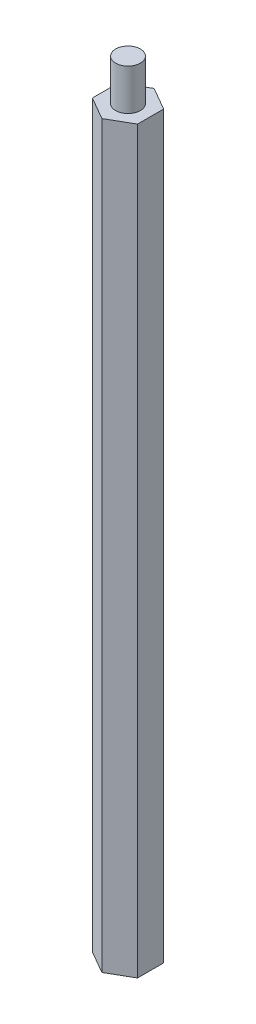
SolidWorks part; units mm, degrees
ref_plane "Front Plane" through (0, 0, 0) normal (0, 0, 1) x (1, 0, 0)
ref_plane "Top Plane" through (0, 0, 0) normal (0, 1, 0) x (1, 0, 0)
ref_plane "Right Plane" through (0, 0, 0) normal (1, 0, 0) x (0, 0, -1)
sketch "Sketch1" plane through (0, 0, 0) normal (0, 1, 0) x (1, 0, 0)
  line L1 (0, 3.1754) -> (-2.75, 1.5877)
  line L2 (-2.75, 1.5877) -> (-2.75, -1.5877)
  line L3 (-2.75, -1.5877) -> (0, -3.1754)
  line L4 (0, -3.1754) -> (2.75, -1.5877)
  line L5 (2.75, -1.5877) -> (2.75, 1.5877)
  line L6 (2.75, 1.5877) -> (0, 3.1754)
  circle A0 centre (0, 0) radius 2.75 construction
  dimension "D1" = 5.5
extrude "Boss-Extrude1" add sketch "Sketch1" along normal blind 90
sketch "Sketch2" plane through (0, 90, 0) normal (0, 1, 0) x (1, 0, 0)
  circle A0 centre (0, 0) radius 1.5
  dimension "D1" = 3
extrude "Boss-Extrude2" add sketch "Sketch2" along normal blind 5
